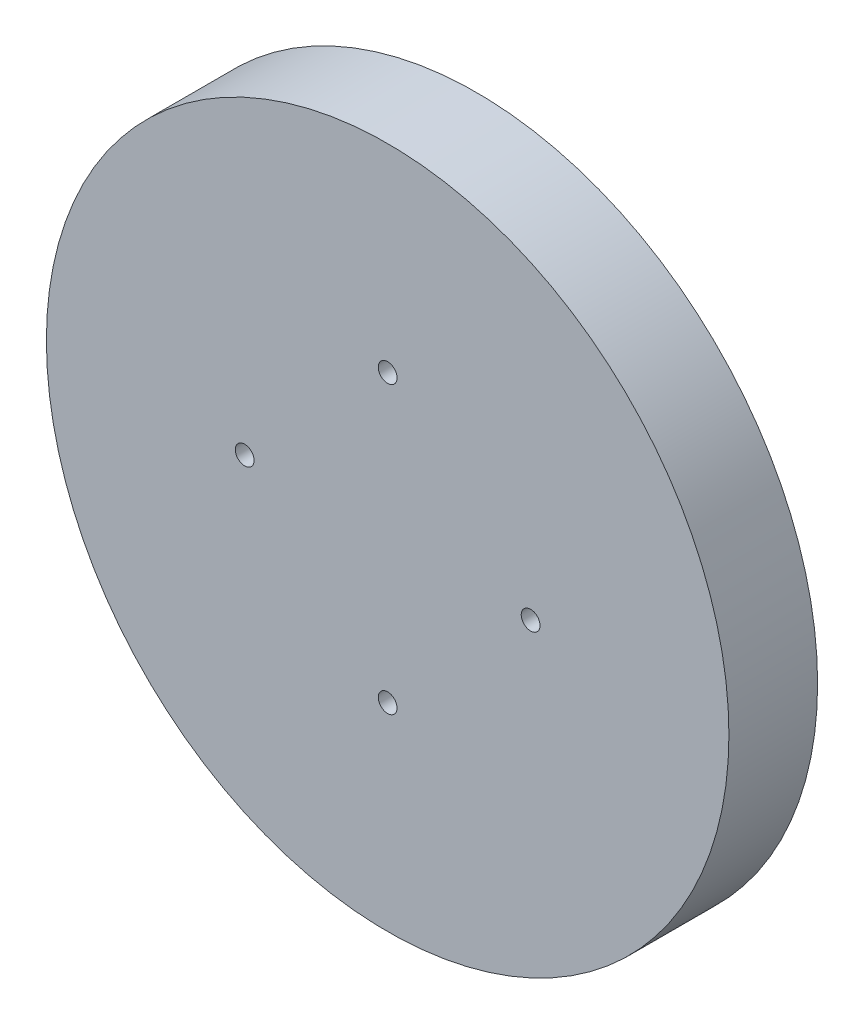
SolidWorks part; units mm, degrees
ref_plane "Plan de face" through (0, 0, 0) normal (0, 0, 1) x (1, 0, 0)
ref_plane "Plan de dessus" through (0, 0, 0) normal (0, 1, 0) x (1, 0, 0)
ref_plane "Plan de droite" through (0, 0, 0) normal (1, 0, 0) x (0, 0, -1)
sketch "Esquisse1" plane through (0, 0, 0) normal (0, 0, 1) x (1, 0, 0)
  circle A0 centre (0, 0) radius 19.24
  dimension "D1" = 38.48
extrude "Boss.-Extru.1" add sketch "Esquisse1" along normal blind 5
sketch "Esquisse2" plane through (0, 0, 5) normal (0, 0, 1) x (1, 0, 0)
  line L0 (0, 0) -> (0, 2.1842) construction
  circle A0 centre (0, 8.06) radius 0.53
  dimension "D2" = 1.06
  dimension "D1" = 8.06
extrude "Enlèv. mat.-Extru.1" cut sketch "Esquisse2" against normal up to surface (5 mm away) up to face at (19.24, 0, 0)
pattern_circular "Répétition circulaire1" count 4 over 360 about axis through (0, 0, 0) along (0, 0, 1) of "Enlèv. mat.-Extru.1"
